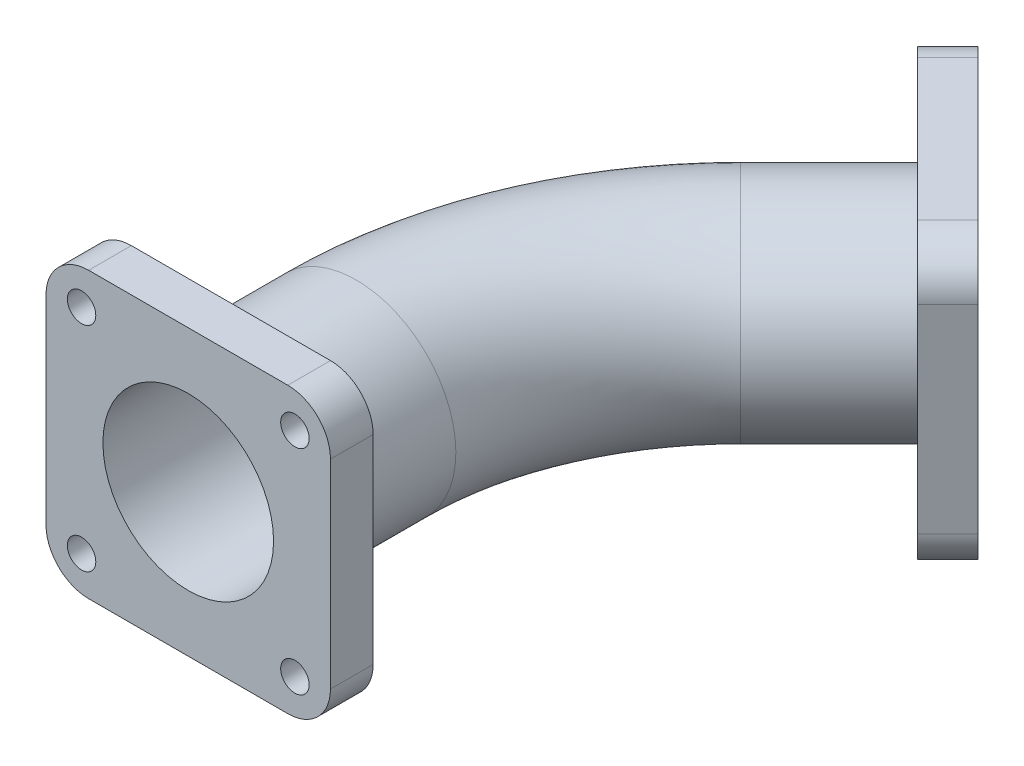
SolidWorks part; units mm, degrees
ref_plane "Alzado" through (0, 0, 0) normal (0, 0, 1) x (1, 0, 0)
ref_plane "Planta" through (0, 0, 0) normal (0, 1, 0) x (1, 0, 0)
ref_plane "Vista lateral" through (0, 0, 0) normal (1, 0, 0) x (0, 0, -1)
sketch "Croquis1" plane through (0, 0, 0) normal (0, 0, 1) x (1, 0, 0)
  line L1 (-50, -50) -> (50, -50)
  line L2 (-50, -50) -> (-50, 50)
  line L3 (-50, 50) -> (50, 50)
  line L4 (50, -50) -> (50, 50)
  line L5 (-50, -50) -> (50, 50) construction
  line L6 (-50, 50) -> (50, -50) construction
  point P0 (0, 0)
  dimension "D1" = 100
  dimension "D2" = 100
extrude "Saliente-Extruir1" add sketch "Croquis1" along normal blind 15
sketch "Croquis2" plane through (0, 0, 0) normal (0, 0, 1) x (1, 0, 0)
  circle A0 centre (0, 0) radius 30
  circle A1 centre (-37.5, 37.5) radius 5
  circle A2 centre (37.5, 37.5) radius 5
  circle A3 centre (37.5, -37.5) radius 5
  circle A4 centre (-37.5, -37.5) radius 5
extrude "Cortar-Extruir1" cut sketch "Croquis2" along normal blind 15
sketch "Croquis3" plane through (0, 0, 0) normal (0, 1, 0) x (1, 0, 0)
  line L0 (0, 0) -> (0, 44.0812)
  line L1 (39.5406, 139.5406) -> (70.7107, 170.7107)
  arc A0 (0, 44.0812) -> (39.5406, 139.5406) centre (135, 44.0812) cw
  point P3 (0, 0)
  point P7 (0, 0)
  dimension "D1" = 135
sketch "Croquis9" plane through (0, 0, 0) normal (0, 0, 1) x (1, 0, 0)
  circle A0 centre (0, 0) radius 30
  circle A1 centre (0, 0) radius 35
sweep "Barrer1" add profiles "Croquis9" path "Croquis3"
sketch "Croquis11" plane through (0, 0, 0) normal (0, 1, 0) x (1, 0, 0)
  line L0 (70.7107, 170.7107) -> (0, 241.4214) construction
  line L1 (95.4594, 145.9619) -> (45.9619, 195.4594) construction
  line L2 (0, 241.4214) -> (141.9417, 99.4797) construction
ref_plane "Plano1" through (120.7107, 0, -120.7107) normal (0.7071, 0, -0.7071) x (-0.7071, 0, -0.7071)
sketch "Croquis12" plane through (120.7107, 0, -120.7107) normal (0.7071, 0, -0.7071) x (-0.7071, 0, -0.7071)
  line L1 (20.7107, 50) -> (120.7107, 50)
  line L2 (20.7107, 50) -> (20.7107, -50)
  line L3 (20.7107, -50) -> (120.7107, -50)
  line L4 (120.7107, 50) -> (120.7107, -50)
  line L5 (20.7107, 50) -> (120.7107, -50) construction
  line L6 (20.7107, -50) -> (120.7107, 50) construction
  point P0 (70.7107, 0)
  dimension "D1" = 100
  dimension "D2" = 100
extrude "Saliente-Extruir2" add sketch "Croquis12" along normal blind 15
sketch "Croquis13" plane through (120.7107, 0, -120.7107) normal (0.7071, 0, -0.7071) x (-0.7071, 0, -0.7071)
  circle A0 centre (70.7107, 0) radius 30
  circle A1 centre (108.2107, 37.5) radius 5
  circle A2 centre (108.2107, -37.5) radius 5
  circle A3 centre (33.2107, -37.5) radius 5
  circle A4 centre (33.2107, 37.5) radius 5
extrude "Cortar-Extruir2" cut sketch "Croquis13" along normal blind 15
fillet "Redondeo1" radius 15 8 edges at (50, 50, 7.5) (-50, 50, 7.5) (-50, -50, 7.5) (50, -50, 7.5) (40.6586, 50, -211.3693) (40.6586, -50, -211.3693) (111.3693, 50, -140.6586) (111.3693, -50, -140.6586)
